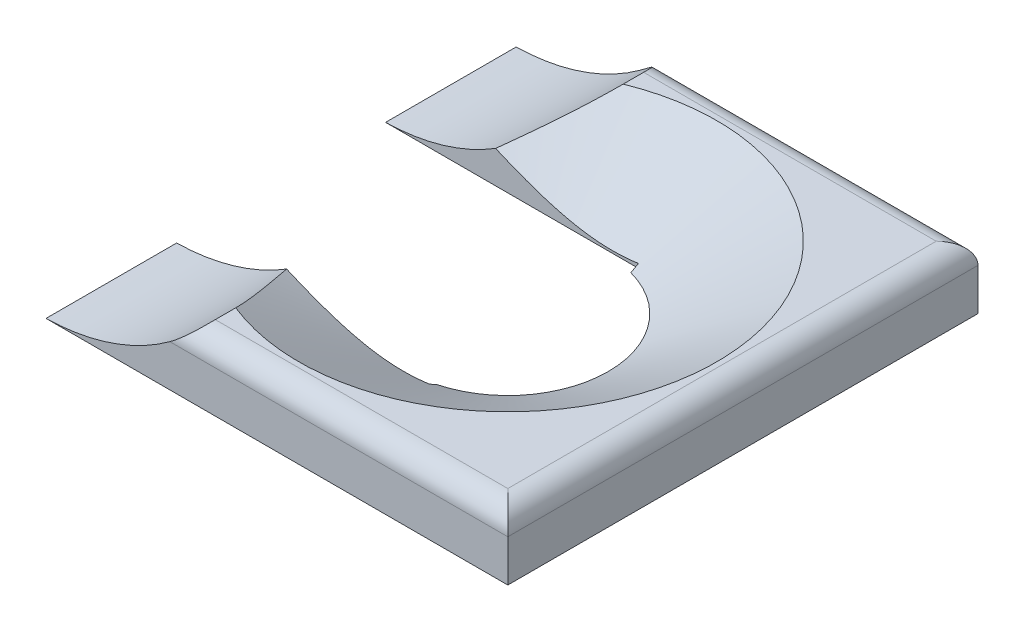
SolidWorks part; units mm, degrees
ref_plane "Front Plane" through (0, 0, 0) normal (0, 0, 1) x (1, 0, 0)
ref_plane "Top Plane" through (0, 0, 0) normal (0, 1, 0) x (1, 0, 0)
ref_plane "Right Plane" through (0, 0, 0) normal (1, 0, 0) x (0, 0, -1)
sketch "Sketch1" plane through (0, 0, 0) normal (0, 1, 0) x (1, 0, 0)
  line L1 (0, 0) -> (45, 0)
  line L2 (0, 0) -> (0, 45)
  line L3 (0, 45) -> (45, 45)
  line L4 (45, 0) -> (45, 45)
  dimension "D1" = 45
  dimension "D2" = 45
extrude "Boss-Extrude1" add sketch "Sketch1" against normal blind 6 contours L2 L3 L4 L1
sketch "Sketch2" plane through (0, 0, 0) normal (0, 1, 0) x (1, 0, 0)
  line L0 (0, 22.5) -> (50000, 22.5) construction
  line L1 (0, 0) -> (0, 45) construction
  line L2 (22.5, 45) -> (22.5, -49955) construction
  line L3 (0, 45) -> (45, 45) construction
  circle A0 centre (22.5, 22.5) radius 20
  point P4 (0, 22.5)
  point P9 (22.5, 45)
  dimension "D1" = 40
  dimension "D2" = 22.5
extrude "Cut-Extrude1" cut sketch "Sketch2" against normal blind 6 draft 60
fillet "Fillet2" radius 2 3 edges at (45, 0, -22.5) (22.5, 0, 0) (22.5, 0, -45)
ref_plane "Plane1" through (25.5, -25.5, 0) normal (0.7071, -0.7071, 0) x (0, 0, -1)
sketch "Sketch3" plane through (25.5, -25.5, 0) normal (0.7071, -0.7071, 0) x (0, 0, -1)
  line L0 (0, 27.5772) -> (0, 31.3272)
  line L1 (0, 31.3272) -> (45, 31.3272)
  line L2 (45, 31.3272) -> (45, 27.5772)
  line L3 (45, 27.5772) -> (0, 27.5772)
sketch "Sketch4" plane through (0, 0, 0) normal (0, 0, 1) x (1, 0, 0)
  line L0 (0, 0) -> (15, 0)
  line L1 (0, 0) -> (43, 0) construction
  line L2 (0, -6) -> (0, 0)
  arc A0 (15, 0) -> (0, -6) centre (0.3998, 14.7505) cw
  dimension "D1" = 20.7543
  dimension "D2" = 15
extrude "Cut-Extrude2" cut sketch "Sketch4" against normal blind 1000
sketch "Sketch5" plane through (0, 0, 0) normal (1, 0, 0) x (0, 0, -1)
  line L0 (12.5, -6) -> (32.5, -6) construction
  line L1 (45, -6) -> (0, -6) construction
  line L2 (42.5, 0) -> (2.5, 0) construction
  line L3 (32.5, -6) -> (12.5, -6)
  line L4 (32.5, -6) -> (32.5, 0)
  line L5 (32.5, 0) -> (12.5, 0)
  line L6 (12.5, -6) -> (12.5, 0)
  point P5 (22.5, -6)
  dimension "D1" = 20
  dimension "D2" = 12.5
extrude "Cut-Extrude3" cut sketch "Sketch5" along normal blind 25
